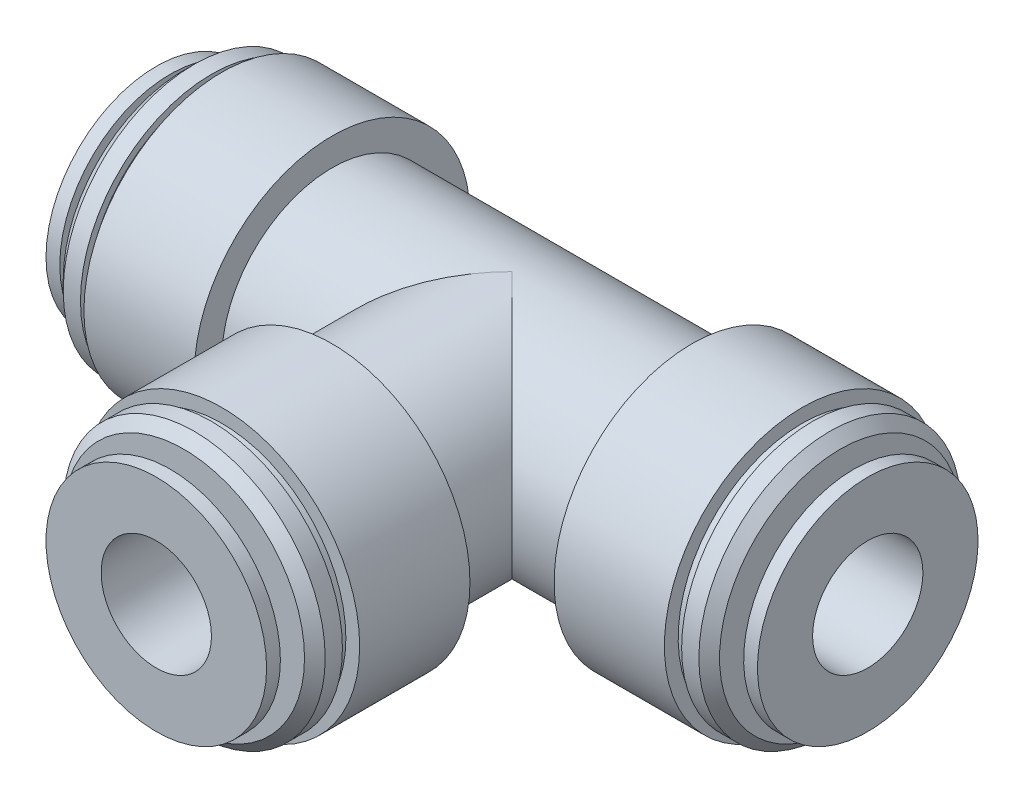
SolidWorks part; units mm, degrees
ref_plane "Спереди" through (0, 0, 0) normal (0, 0, 1) x (1, 0, 0)
ref_plane "Сверху" through (0, 0, 0) normal (0, 1, 0) x (1, 0, 0)
ref_plane "Справа" through (0, 0, 0) normal (1, 0, 0) x (0, 0, -1)
sketch "Эскиз1" plane through (0, 0, 0) normal (0, 0, 1) x (1, 0, 0)
  line L0 (-16.75, -8) -> (-16.75, -6)
  line L1 (-17.75, -4) -> (-17.75, -8)
  line L2 (-13, -9) -> (-13, -10)
  line L3 (-17.75, -8) -> (-16.75, -8)
  line L4 (-15.75, -6) -> (-15.75, -8.75)
  line L5 (-15, -9.5) -> (-13.75, -9.5)
  line L6 (-15.75, -8.75) -> (-15, -9.5)
  line L7 (-13.75, -9.5) -> (-13.75, -9)
  line L8 (-13.75, -9) -> (-13, -9)
  line L9 (-17.75, -4) -> (-5, -4)
  line L10 (-16.75, -6) -> (-15.75, -6)
  line L11 (-13, -10) -> (-5, -10)
  line L12 (-5, -10) -> (-5, -4)
  line L13 (-21.0495, 0) -> (4.2526, 0) construction
  point P5 (-15.75, -9.5)
  dimension "D1" = 0.75
  dimension "D2" = 0.75
revolve "Повернуть1" add sketch "Эскиз1" angle 360 about L13
sketch "Эскиз2" plane through (-5, 0, 0) normal (1, 0, 0) x (0, 0, -1)
  circle A0 centre (0, 0) radius 8
  circle A1 centre (0, 0) radius 4
extrude "Бобышка-Вытянуть1" add sketch "Эскиз2" along normal blind 26.1
sketch "Эскиз3" plane through (0, 0, 0) normal (0, 0, 1) x (1, 0, 0)
  line L0 (32.85, 8) -> (32.85, 6)
  line L1 (33.85, 4) -> (33.85, 8)
  line L2 (29.1, 9) -> (29.1, 10)
  line L3 (33.85, 8) -> (32.85, 8)
  line L4 (31.85, 6) -> (31.85, 8.75)
  line L5 (31.1, 9.5) -> (29.85, 9.5)
  line L6 (31.85, 8.75) -> (31.1, 9.5)
  line L7 (29.85, 9.5) -> (29.85, 9)
  line L8 (29.85, 9) -> (29.1, 9)
  line L9 (33.85, 4) -> (21.1, 4)
  line L10 (32.85, 6) -> (31.85, 6)
  line L11 (29.1, 10) -> (21.1, 10)
  line L12 (21.1, 10) -> (21.1, 4)
  line L13 (47.1495, 0) -> (14.4859, 0) construction
  line L14 (21.1, -8) -> (21.1, 8) construction
  point P5 (31.85, 9.5)
  dimension "D1" = 0.75
  dimension "D2" = 0.75
  dimension "D3" = 0.75
  dimension "D4" = 2.75
  dimension "D5" = 1.25
  dimension "D6" = 1
  dimension "D7" = 1
revolve "Повернуть2" add sketch "Эскиз3" angle 360 about L13
sketch "Эскиз4" plane through (0, 0, 0) normal (0, 0, 1) x (1, 0, 0)
  circle A0 centre (8.05, 0) radius 8
extrude "Бобышка-Вытянуть2" add sketch "Эскиз4" along normal blind 13.05
sketch "Эскиз5" plane through (0, 0, 0) normal (0, 1, 0) x (1, 0, 0)
  line L0 (16.05, -24.8) -> (14.05, -24.8)
  line L1 (12.05, -25.8) -> (16.05, -25.8)
  line L2 (17.05, -21.05) -> (18.05, -21.05)
  line L3 (16.05, -25.8) -> (16.05, -24.8)
  line L4 (14.05, -23.8) -> (16.8, -23.8)
  line L5 (17.55, -23.05) -> (17.55, -21.8)
  line L6 (16.8, -23.8) -> (17.55, -23.05)
  line L7 (17.55, -21.8) -> (17.05, -21.8)
  line L8 (17.05, -21.8) -> (17.05, -21.05)
  line L9 (12.05, -25.8) -> (12.05, -13.05)
  line L10 (14.05, -24.8) -> (14.05, -23.8)
  line L11 (18.05, -21.05) -> (18.05, -13.05)
  line L12 (18.05, -13.05) -> (12.05, -13.05)
  line L13 (8.05, -29.0995) -> (8.05, -3.7974) construction
  point P5 (17.55, -23.8)
  dimension "D1" = 0.75
  dimension "D2" = 0.75
revolve "Повернуть3" add sketch "Эскиз5" angle 360 about L13
sketch "Эскиз6" plane through (-17.75, 0, 0) normal (-1, 0, 0) x (0, 0, 1)
  circle A0 centre (0, 0) radius 4
  dimension "D1" = 8
extrude "Вырез-Вытянуть1" cut sketch "Эскиз6" against normal blind 63.05
sketch "Эскиз7" plane through (0, 0, 25.8) normal (0, 0, 1) x (1, 0, 0)
  circle A0 centre (8.05, 0) radius 4
  dimension "D1" = 8
extrude "Вырез-Вытянуть2" cut sketch "Эскиз7" against normal blind 25
